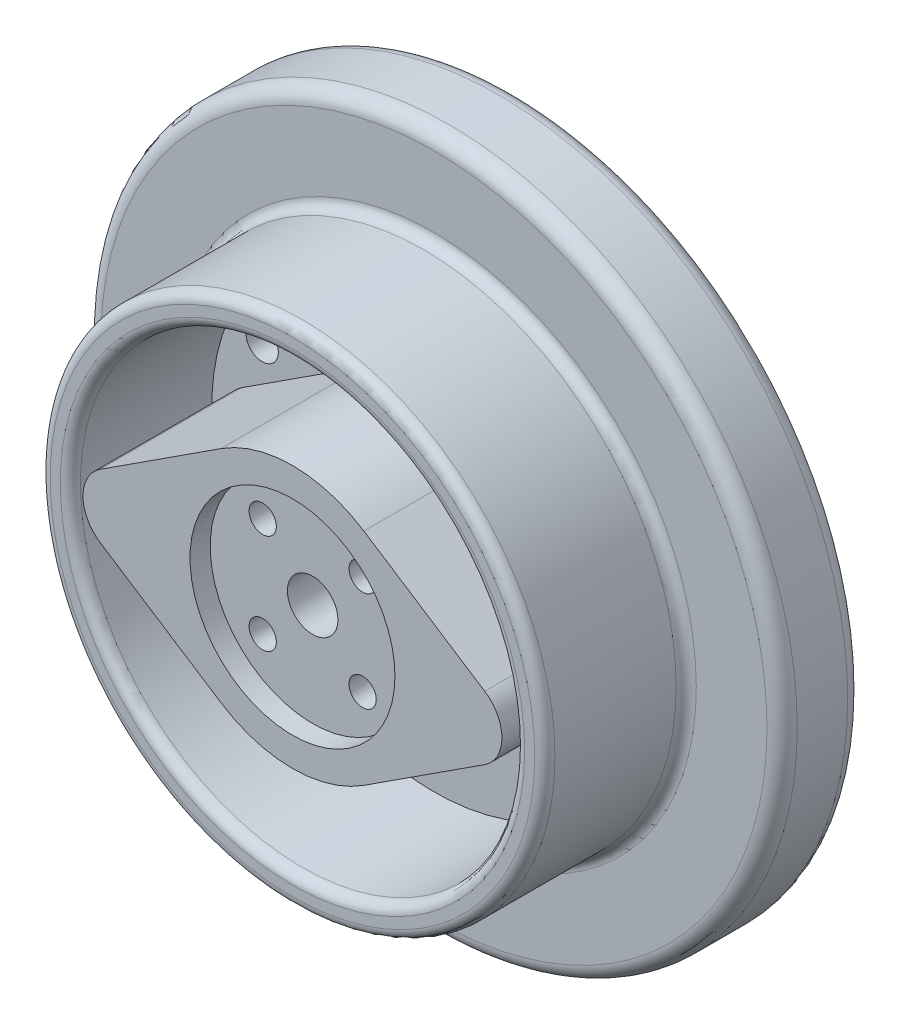
SolidWorks part; units mm, degrees
material "ABS"
ref_plane "前视基准面" through (0, 0, 0) normal (0, 0, 1) x (1, 0, 0)
ref_plane "上视基准面" through (0, 0, 0) normal (0, 1, 0) x (1, 0, 0)
ref_plane "右视基准面" through (0, 0, 0) normal (1, 0, 0) x (0, 0, -1)
sketch "草图1" plane through (0, 0, 0) normal (0, 0, 1) x (1, 0, 0)
  circle A0 centre (0, 0) radius 34.5
  dimension "D1" = 69
extrude "凸台-拉伸1" add sketch "草图1" along normal blind 8
sketch "草图2" plane through (0, 0, 8) normal (0, 0, 1) x (1, 0, 0)
  circle A0 centre (0, 0) radius 25
  circle A1 centre (0, 0) radius 22
  dimension "D1" = 50
  dimension "D2" = 44
extrude "凸台-拉伸2" add sketch "草图2" along normal blind 14
fillet "圆角1" radius 1 1 edges at (25, 0, 8)
sketch "草图3" plane through (0, 0, 8) normal (0, 0, 1) x (1, 0, 0)
  circle A0 centre (0, 0) radius 10.15
  circle A1 centre (0, 0) radius 13
  dimension "D1" = 20.3
  dimension "D2" = 26
extrude "凸台-拉伸3" add sketch "草图3" along normal blind 14
sketch "草图4" plane through (0, 0, 8) normal (0, 0, 1) x (1, 0, 0)
  line L0 (0, 0) -> (34, 0) construction
  line L1 (0, 0) -> (0, 58.4157) construction
  line L2 (17, 0) -> (17, 9.2157) construction
  line L3 (3.6, 0) -> (3.6, -7.25) construction
  circle A0 centre (-17, 8) radius 1.6
  circle A1 centre (17, 0) radius 2.55
  circle A3 centre (0, 0) radius 4
  circle A6 centre (-17, -8) radius 1.6
  circle A7 centre (17, -8) radius 1.6
  circle A8 centre (17, 8) radius 1.6
  circle A9 centre (-17, 0) radius 2.55
  circle A10 centre (3.6, -7.25) radius 0.85
  circle A11 centre (3.6, 7.25) radius 0.85
  circle A12 centre (-3.6, 7.25) radius 0.85
  circle A13 centre (-3.6, -7.25) radius 0.85
  dimension "D1" = 8
  dimension "D3" = 5.1
  dimension "D4" = 3.2
  dimension "D5" = 8
  dimension "D6" = 7.25
  dimension "D8" = 1.7
  dimension "D2" = 17
  dimension "D7" = 3.6
extrude "切除-拉伸1" cut sketch "草图4" against normal through all contours A9 | A0 | A6 | A7 | A1 | A8
sketch "草图7" plane through (0, 0, 8) normal (0, 0, 1) x (1, 0, 0)
  circle A0 centre (0, 0) radius 10.5
extrude "凸台-拉伸5" add sketch "草图7" along normal blind 12 contours A0
sketch "草图8" plane through (0, 0, 0) normal (0, 0, -1) x (-1, 0, 0)
  arc A0 (8.6168, -6) -> (-8.6168, -6) centre (0, 0) ccw
  arc A1 (-8.6168, -6) -> (8.6168, -6) centre (0, 0) ccw
  dimension "D1" = 21
extrude "切除-拉伸2" cut sketch "草图8" against normal offset from surface (15 mm away) 5 up to face at (10.15, 0, 20)
sketch "草图9" plane through (0, 0, 20) normal (0, 0, 1) x (1, 0, 0)
  line L0 (0, 0) -> (17.1066, 0) construction
  line L1 (4.9497, 0) -> (4.9497, 4.9497) construction
  line L2 (0, 0) -> (0, 16.7273) construction
  line L3 (4.9497, 4.9497) -> (0, 0) construction
  circle A0 centre (0, 0) radius 2.5
  circle A1 centre (4.9497, 4.9497) radius 1.35
  circle A2 centre (-4.9497, 4.9497) radius 1.35
  circle A3 centre (-4.9497, -4.9497) radius 1.35
  circle A4 centre (4.9497, -4.9497) radius 1.35
  dimension "D1" = 5
  dimension "D2" = 2.7
  dimension "D3" = 45
  dimension "D4" = 14
extrude "切除-拉伸3" cut sketch "草图9" against normal through all
sketch "草图10" plane through (0, 0, 8) normal (0, 0, 1) x (1, 0, 0)
  line L0 (7.0735, 10.9071) -> (19.0404, 3.1463)
  line L1 (19.0404, -3.1463) -> (7.0735, -10.9071)
  line L2 (0, 0) -> (0, 14.9045) construction
  line L3 (-19.0404, -3.1463) -> (-7.0735, -10.9071)
  line L4 (-7.0735, 10.9071) -> (-19.0404, 3.1463)
  arc A0 (19.0404, -3.1463) -> (19.0404, 3.1463) centre (17, 0) ccw
  circle A3 centre (17, 0) radius 2.55 construction
  circle A5 centre (17, 0) radius 2.55
  circle A6 centre (0, 0) radius 13 construction
  circle A7 centre (0, 0) radius 13 construction
  arc A8 (-7.0735, 10.9071) -> (-7.0735, -10.9071) centre (0, 0) ccw
  circle A9 centre (-17, 0) radius 2.55
  arc A10 (-19.0404, -3.1463) -> (-19.0404, 3.1463) centre (-17, 0) cw
  arc A11 (7.0735, -10.9071) -> (7.0735, 10.9071) centre (0, 0) ccw
  dimension "D1" = 7.5
extrude "凸台-拉伸6" add sketch "草图10" along normal blind 14
sketch "草图11" plane through (0, 0, 22) normal (0, 0, 1) x (1, 0, 0)
  circle A1 centre (17, 0) radius 2.55 construction
  circle A2 centre (-17, 0) radius 2.55
  circle A3 centre (17, 0) radius 2.55
  circle A4 centre (-17, 0) radius 2.55 construction
  dimension "D1" = 5.1
extrude "凸台-拉伸7" add sketch "草图11" against normal blind 3
fillet "圆角2" radius 1 2 edges at (22, 0, 22) (25, 0, 22)
fillet "圆角3" radius 1.5 2 edges at (34.5, 0, 8) (34.5, 0, 0)
sketch "草图12" plane through (0, 0, 8) normal (0, 0, 1) x (1, 0, 0)
  line L0 (0, 0) -> (0, 19.5589) construction
  circle A0 centre (0, 18) radius 1.65
  circle A1 centre (0, -18) radius 1.65
  dimension "D1" = 3.3
  dimension "D2" = 3.3
  dimension "D3" = 18
  dimension "D4" = 18
extrude "切除-拉伸4" cut sketch "草图12" against normal blind 10
sketch "草图13" plane through (0, 0, 19) normal (0, 0, -1) x (-1, 0, 0)
  circle A0 centre (-17, 0) radius 2.55 construction
  circle A1 centre (17, 0) radius 2.55 construction
  circle A2 centre (-17, 0) radius 2.55
  circle A3 centre (17, 0) radius 2.55
extrude "凸台-拉伸8" [suppressed] add sketch "草图13" along normal blind 5
